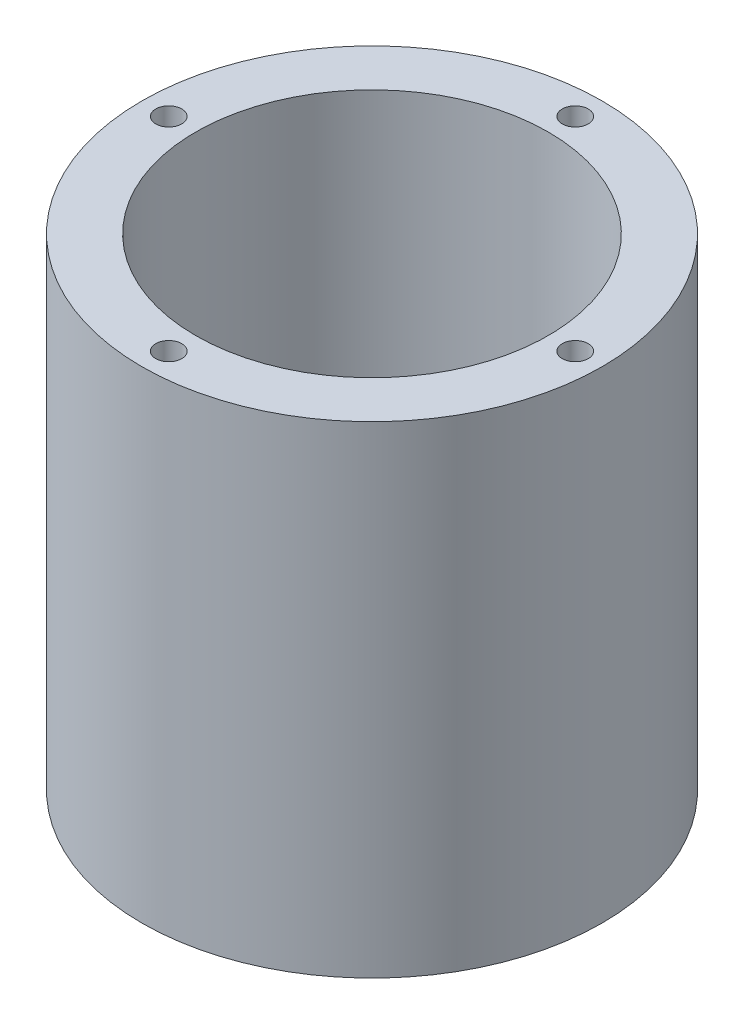
SolidWorks part; units mm, degrees
ref_plane "Front Plane" through (0, 0, 0) normal (0, 0, 1) x (1, 0, 0)
ref_plane "Top Plane" through (0, 0, 0) normal (0, 1, 0) x (1, 0, 0)
ref_plane "Right Plane" through (0, 0, 0) normal (1, 0, 0) x (0, 0, -1)
sketch "Sketch1" plane through (0, 0, 0) normal (0, 1, 0) x (1, 0, 0)
  circle A0 centre (0, 0) radius 15.65 construction
  circle A1 centre (16.6, 0) radius 0.95
  circle A2 centre (0, -16.6) radius 0.95
  circle A3 centre (-16.6, 0) radius 0.95
  circle A4 centre (0, 16.6) radius 0.95
  circle A5 centre (0, 0) radius 19.65
  circle A6 centre (0, 0) radius 4
  circle A7 centre (0, 0) radius 25.65
  point P14 (0, 0)
  dimension "D1" = 31.3
  dimension "D2" = 1.9
  dimension "D5" = 8
  dimension "D4" = 4
  dimension "D6" = 6
  dimension "D3" = 4
extrude "Boss-Extrude1" add sketch "Sketch1" along normal blind 3.7 contours A7 A5 | A5 A6 A1 A2 A3 A4
sketch "Sketch2" plane through (0, 3.7, 0) normal (0, 1, 0) x (1, 0, 0)
  circle A1 centre (0, 0) radius 25.65
  circle A2 centre (0, 0) radius 25.65
  circle A3 centre (0, 0) radius 4
  circle A4 centre (0, 0) radius 4
  circle A5 centre (0, 0) radius 19.65
  circle A6 centre (0, 0) radius 19.65
  circle A7 centre (0, 16.6) radius 0.95
  circle A8 centre (0, 16.6) radius 0.95
  circle A9 centre (-16.6, 0) radius 0.95
  circle A10 centre (-16.6, 0) radius 0.95
  circle A11 centre (0, -16.6) radius 0.95
  circle A12 centre (0, -16.6) radius 0.95
  circle A13 centre (16.6, 0) radius 0.95
  circle A14 centre (16.6, 0) radius 0.95
  circle A15 centre (0, 0) radius 25.65
  circle A16 centre (0, 0) radius 25.65
  circle M9 centre (0, 0) radius 25.65
  dimension "D1" = 0
  dimension "D2" = 0
  dimension "D3" = 0
  dimension "D4" = 0
  dimension "D5" = 0
  dimension "D6" = 0
  dimension "D7" = 0
  dimension "D8" = 0
extrude "Boss-Extrude2" add sketch "Sketch2" along normal blind 50 contours A6 M9 | A2
sketch "Sketch3" plane through (0, 53.7, 0) normal (0, 1, 0) x (1, 0, 0)
  line L0 (19.65, 0) -> (25.65, 0) construction
  circle A0 centre (0, 0) radius 19.65 construction
  circle A1 centre (0, 0) radius 19.65 construction
  circle A2 centre (0, 0) radius 25.65 construction
  circle A3 centre (22.65, 0) radius 1.45
  circle A4 centre (0, -22.65) radius 1.45
  circle A5 centre (-22.65, 0) radius 1.45
  circle A6 centre (0, 22.65) radius 1.45
  point P20 (0, 0)
  dimension "D1" = 2.9
  dimension "D2" = 4
extrude "Cut-Extrude1" cut sketch "Sketch3" against normal blind 15
